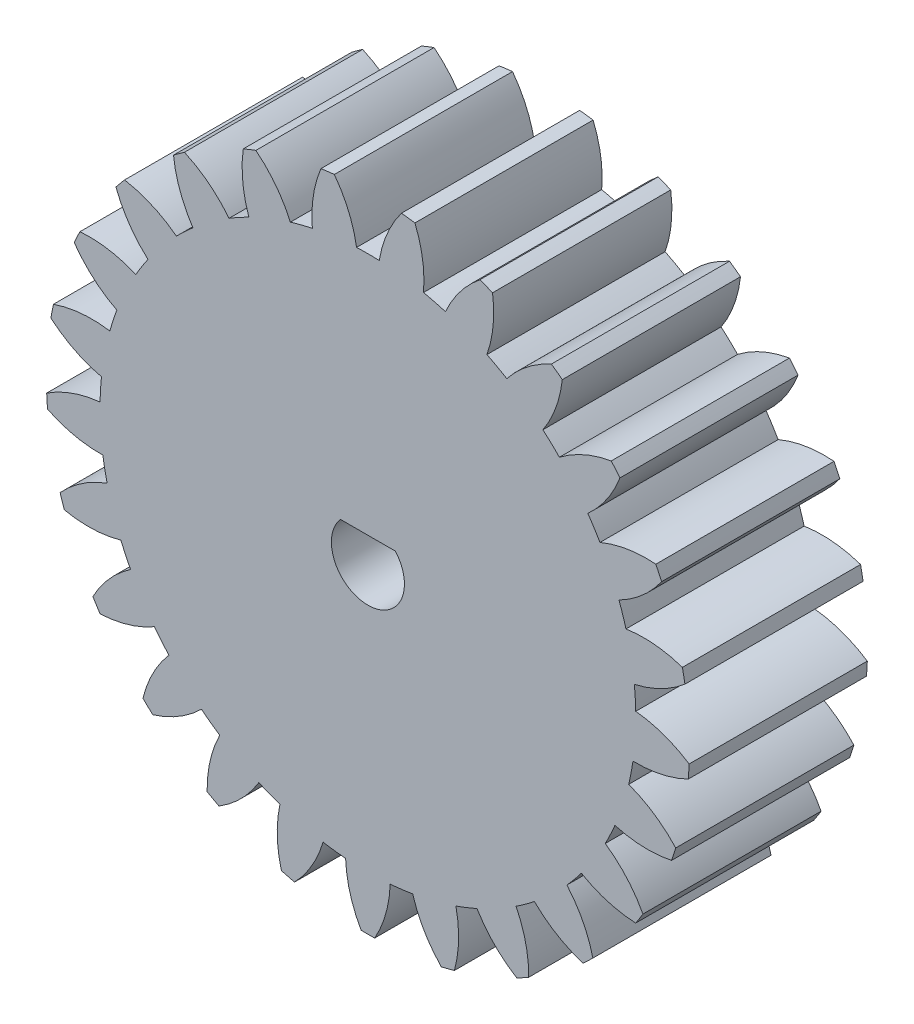
SolidWorks part; units mm, degrees
ref_plane "Front Plane" through (0, 0, 0) normal (0, 0, 1) x (1, 0, 0)
ref_plane "Top Plane" through (0, 0, 0) normal (0, 1, 0) x (1, 0, 0)
ref_plane "Right Plane" through (0, 0, 0) normal (1, 0, 0) x (0, 0, -1)
sketch "Sketch1" plane through (0, 0, 0) normal (0, 0, 1) x (1, 0, 0)
  line L0 (-1.5427, 1.35) -> (1.5427, 1.35)
  arc A0 (6.9943, 16.6324) -> (6.287, 16.9124) centre (0, 0) ccw
  arc A1 (6.287, 16.9124) -> (4.3519, 14.3915) centre (10.4683, 11.6995) ccw
  arc A2 (4.3519, 14.3915) -> (3.1196, 14.7079) centre (0, 0) ccw
  arc A3 (3.1196, 14.7079) -> (2.6383, 17.8493) centre (-3.5372, 15.2954) ccw
  arc A4 (2.6383, 17.8493) -> (1.8836, 17.9446) centre (0, 0) ccw
  arc A5 (1.8836, 17.9446) -> (0.6361, 15.0216) centre (7.2299, 13.9352) ccw
  arc A6 (0.6361, 15.0216) -> (-0.6361, 15.0216) centre (0, 0) ccw
  arc A7 (-0.6361, 15.0216) -> (-1.8836, 17.9446) centre (-7.2299, 13.9352) ccw
  arc A8 (-1.8836, 17.9446) -> (-2.6383, 17.8493) centre (0, 0) ccw
  arc A9 (-2.6383, 17.8493) -> (-3.1196, 14.7079) centre (3.5372, 15.2954) ccw
  arc A10 (-3.1196, 14.7079) -> (-4.3519, 14.3915) centre (0, 0) ccw
  arc A11 (-4.3519, 14.3915) -> (-6.287, 16.9124) centre (-10.4683, 11.6995) ccw
  arc A12 (-6.287, 16.9124) -> (-6.9943, 16.6324) centre (0, 0) ccw
  arc A13 (-6.9943, 16.6324) -> (-6.6793, 13.47) centre (-0.3778, 15.6946) ccw
  arc A14 (-6.6793, 13.47) -> (-7.7942, 12.8571) centre (0, 0) ccw
  arc A15 (-7.7942, 12.8571) -> (-10.2955, 14.8176) centre (-13.0489, 8.7285) ccw
  arc A16 (-10.2955, 14.8176) -> (-10.9109, 14.3704) centre (0, 0) ccw
  arc A17 (-10.9109, 14.3704) -> (-9.8193, 11.3857) centre (-4.269, 15.1075) ccw
  arc A18 (-9.8193, 11.3857) -> (-10.7467, 10.5149) centre (0, 0) ccw
  arc A19 (-10.7467, 10.5149) -> (-13.657, 11.7917) centre (-14.8097, 5.2092) ccw
  arc A20 (-13.657, 11.7917) -> (-14.1419, 11.2055) centre (0, 0) ccw
  arc A21 (-14.1419, 11.2055) -> (-12.3423, 8.5861) centre (-7.892, 13.5713) ccw
  arc A22 (-12.3423, 8.5861) -> (-13.024, 7.5119) centre (0, 0) ccw
  arc A23 (-13.024, 7.5119) -> (-16.1604, 8.0249) centre (-15.6399, 1.3625) ccw
  arc A24 (-16.1604, 8.0249) -> (-16.4843, 7.3366) centre (0, 0) ccw
  arc A25 (-16.4843, 7.3366) -> (-14.0899, 5.2469) centre (-11.0191, 11.1822) ccw
  arc A26 (-14.0899, 5.2469) -> (-14.483, 4.037) centre (0, 0) ccw
  arc A27 (-14.483, 4.037) -> (-17.6484, 3.7538) centre (-15.4874, -2.5698) ccw
  arc A28 (-17.6484, 3.7538) -> (-17.7909, 3.0066) centre (0, 0) ccw
  arc A29 (-17.7909, 3.0066) -> (-14.952, 1.5781) centre (-13.4538, 8.0906) ccw
  arc A30 (-14.952, 1.5781) -> (-15.0319, 0.3084) centre (0, 0) ccw
  arc A31 (-15.0319, 0.3084) -> (-18.0275, -0.7531) centre (-14.3617, -6.3406) ccw
  arc A32 (-18.0275, -0.7531) -> (-17.9797, -1.5123) centre (0, 0) ccw
  arc A33 (-17.9797, -1.5123) -> (-14.8748, -2.1899) centre (-15.0432, 4.4906) ccw
  arc A34 (-14.8748, -2.1899) -> (-14.6364, -3.4396) centre (0, 0) ccw
  arc A35 (-14.6364, -3.4396) -> (-17.2738, -5.2127) centre (-12.3337, -9.713) ccw
  arc A36 (-17.2738, -5.2127) -> (-17.0387, -5.9361) centre (0, 0) ccw
  arc A37 (-17.0387, -5.9361) -> (-13.8628, -5.8203) centre (-15.6873, 0.6084) ccw
  arc A38 (-13.8628, -5.8203) -> (-13.3211, -6.9715) centre (0, 0) ccw
  arc A39 (-13.3211, -6.9715) -> (-15.4348, -9.3447) centre (-9.5307, -12.4751) ccw
  arc A40 (-15.4348, -9.3447) -> (-15.0272, -9.987) centre (0, 0) ccw
  arc A41 (-15.0272, -9.987) -> (-11.9798, -9.085) centre (-15.3458, -3.312) ccw
  arc A42 (-11.9798, -9.085) -> (-11.1689, -10.0653) centre (0, 0) ccw
  arc A43 (-11.1689, -10.0653) -> (-12.6259, -12.8896) centre (-6.1288, -14.4534) ccw
  arc A44 (-12.6259, -12.8896) -> (-12.0714, -13.4104) centre (0, 0) ccw
  arc A45 (-12.0714, -13.4104) -> (-9.3441, -11.7789) centre (-14.04, -7.0242) ccw
  arc A46 (-9.3441, -11.7789) -> (-8.3149, -12.5267) centre (0, 0) ccw
  arc A47 (-8.3149, -12.5267) -> (-9.0237, -15.6246) centre (-2.3418, -15.5235) ccw
  arc A48 (-9.0237, -15.6246) -> (-8.3571, -15.9911) centre (0, 0) ccw
  arc A49 (-8.3571, -15.9911) -> (-6.1213, -13.7326) centre (-11.8521, -10.2952) ccw
  arc A50 (-6.1213, -13.7326) -> (-4.9384, -14.2009) centre (0, 0) ccw
  arc A51 (-4.9384, -14.2009) -> (-4.8546, -17.3779) centre (1.5923, -15.6182) ccw
  arc A52 (-4.8546, -17.3779) -> (-4.1178, -17.567) centre (0, 0) ccw
  arc A53 (-4.1178, -17.567) -> (-2.5138, -14.8235) centre (-8.9194, -12.9192) ccw
  arc A54 (-2.5138, -14.8235) -> (-1.2516, -14.9829) centre (0, 0) ccw
  arc A55 (-1.2516, -14.9829) -> (-0.3803, -18.0392) centre (5.4263, -14.7315) ccw
  arc A56 (-0.3803, -18.0392) -> (0.3803, -18.0392) centre (0, 0) ccw
  arc A57 (0.3803, -18.0392) -> (1.2516, -14.9829) centre (-5.4263, -14.7315) ccw
  arc A58 (1.2516, -14.9829) -> (2.5138, -14.8235) centre (0, 0) ccw
  arc A59 (2.5138, -14.8235) -> (4.1178, -17.567) centre (8.9194, -12.9192) ccw
  arc A60 (4.1178, -17.567) -> (4.8546, -17.3779) centre (0, 0) ccw
  arc A61 (4.8546, -17.3779) -> (4.9384, -14.2009) centre (-1.5923, -15.6182) ccw
  arc A62 (4.9384, -14.2009) -> (6.1213, -13.7326) centre (0, 0) ccw
  arc A63 (6.1213, -13.7326) -> (8.3571, -15.9911) centre (11.8521, -10.2952) ccw
  arc A64 (8.3571, -15.9911) -> (9.0237, -15.6246) centre (0, 0) ccw
  arc A65 (9.0237, -15.6246) -> (8.3149, -12.5267) centre (2.3418, -15.5235) ccw
  arc A66 (8.3149, -12.5267) -> (9.3441, -11.7789) centre (0, 0) ccw
  arc A67 (9.3441, -11.7789) -> (12.0714, -13.4104) centre (14.04, -7.0242) ccw
  arc A68 (12.0714, -13.4104) -> (12.6259, -12.8896) centre (0, 0) ccw
  arc A69 (12.6259, -12.8896) -> (11.1689, -10.0653) centre (6.1288, -14.4534) ccw
  arc A70 (11.1689, -10.0653) -> (11.9798, -9.085) centre (0, 0) ccw
  arc A71 (11.9798, -9.085) -> (15.0272, -9.987) centre (15.3458, -3.312) ccw
  arc A72 (15.0272, -9.987) -> (15.4348, -9.3447) centre (0, 0) ccw
  arc A73 (15.4348, -9.3447) -> (13.3211, -6.9715) centre (9.5307, -12.4751) ccw
  arc A74 (13.3211, -6.9715) -> (13.8628, -5.8203) centre (0, 0) ccw
  arc A75 (13.8628, -5.8203) -> (17.0387, -5.9361) centre (15.6873, 0.6084) ccw
  arc A76 (17.0387, -5.9361) -> (17.2738, -5.2127) centre (0, 0) ccw
  arc A77 (17.2738, -5.2127) -> (14.6364, -3.4396) centre (12.3337, -9.713) ccw
  arc A78 (14.6364, -3.4396) -> (14.8748, -2.1899) centre (0, 0) ccw
  arc A79 (14.8748, -2.1899) -> (17.9797, -1.5123) centre (15.0432, 4.4906) ccw
  arc A80 (17.9797, -1.5123) -> (18.0275, -0.7531) centre (0, 0) ccw
  arc A81 (18.0275, -0.7531) -> (15.0319, 0.3084) centre (14.3617, -6.3406) ccw
  arc A82 (15.0319, 0.3084) -> (14.952, 1.5781) centre (0, 0) ccw
  arc A83 (14.952, 1.5781) -> (17.7909, 3.0066) centre (13.4538, 8.0906) ccw
  arc A84 (17.7909, 3.0066) -> (17.6484, 3.7538) centre (0, 0) ccw
  arc A85 (17.6484, 3.7538) -> (14.483, 4.037) centre (15.4874, -2.5698) ccw
  arc A86 (14.483, 4.037) -> (14.0899, 5.2469) centre (0, 0) ccw
  arc A87 (14.0899, 5.2469) -> (16.4843, 7.3366) centre (11.0191, 11.1822) ccw
  arc A88 (16.4843, 7.3366) -> (16.1604, 8.0249) centre (0, 0) ccw
  arc A89 (16.1604, 8.0249) -> (13.024, 7.5119) centre (15.6399, 1.3625) ccw
  arc A90 (13.024, 7.5119) -> (12.3423, 8.5861) centre (0, 0) ccw
  arc A91 (12.3423, 8.5861) -> (14.1419, 11.2055) centre (7.892, 13.5713) ccw
  arc A92 (14.1419, 11.2055) -> (13.657, 11.7917) centre (0, 0) ccw
  arc A93 (13.657, 11.7917) -> (10.7467, 10.5149) centre (14.8097, 5.2092) ccw
  arc A94 (10.7467, 10.5149) -> (9.8193, 11.3857) centre (0, 0) ccw
  arc A95 (9.8193, 11.3857) -> (10.9109, 14.3704) centre (4.269, 15.1075) ccw
  arc A96 (10.9109, 14.3704) -> (10.2955, 14.8176) centre (0, 0) ccw
  arc A97 (10.2955, 14.8176) -> (7.7942, 12.8571) centre (13.0489, 8.7285) ccw
  arc A98 (7.7942, 12.8571) -> (6.6793, 13.47) centre (0, 0) ccw
  arc A99 (6.6793, 13.47) -> (6.9943, 16.6324) centre (0.3778, 15.6946) ccw
  arc A100 (1.5427, 1.35) -> (-1.5427, 1.35) centre (0, 0) cw
  dimension "D1" = 2.05
  dimension "D2" = 1.35
extrude "Boss-Extrude1" add sketch "Sketch1" along normal blind 10
